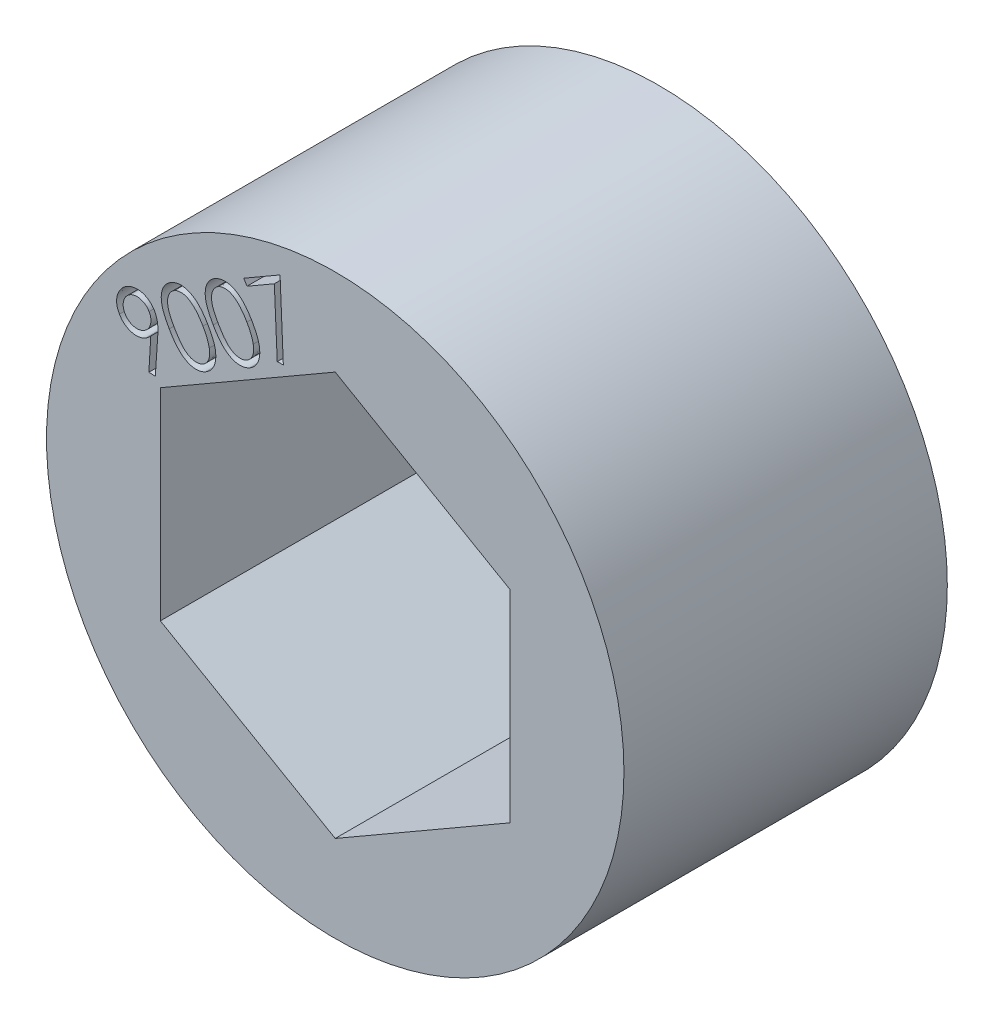
SolidWorks part; units mm, degrees
material "ABS"
ref_plane "Front Plane" through (0, 0, 0) normal (0, 0, 1) x (1, 0, 0)
ref_plane "Top Plane" through (0, 0, 0) normal (0, 1, 0) x (1, 0, 0)
ref_plane "Right Plane" through (0, 0, 0) normal (1, 0, 0) x (0, 0, -1)
sketch "Sketch1" plane through (0, 0, 0) normal (0, 0, 1) x (1, 0, 0)
  line L1 (0, 7.7723) -> (-6.731, 3.8861)
  line L2 (-6.731, 3.8861) -> (-6.731, -3.8861)
  line L3 (-6.731, -3.8861) -> (0, -7.7723)
  line L4 (0, -7.7723) -> (6.731, -3.8861)
  line L5 (6.731, -3.8861) -> (6.731, 3.8861)
  line L6 (6.731, 3.8861) -> (0, 7.7723)
  circle A0 centre (0, 0) radius 6.731 construction
  circle A1 centre (0, 0) radius 11.1125
  dimension "D1" = 13.462
  dimension "D2" = 22.225
extrude "Boss-Extrude1" add sketch "Sketch1" along normal blind 12.446 contours A1 L6 L5 L4 L3 L2 L1
sketch "Sketch2" plane through (0, 0, 12.446) normal (0, 0, 1) x (1, 0, 0)
  line L0 (-7.5438, 3.8861) -> (-0.8128, 7.7723) construction
  line L1 (0, 7.7723) -> (-6.731, 3.8861) construction
  text T0 "9007\r\n" font "Century Gothic" height 2.54
  dimension "D1" = 0.4064
extrude "Cut-Extrude1" cut sketch "Sketch2" against normal blind 2
